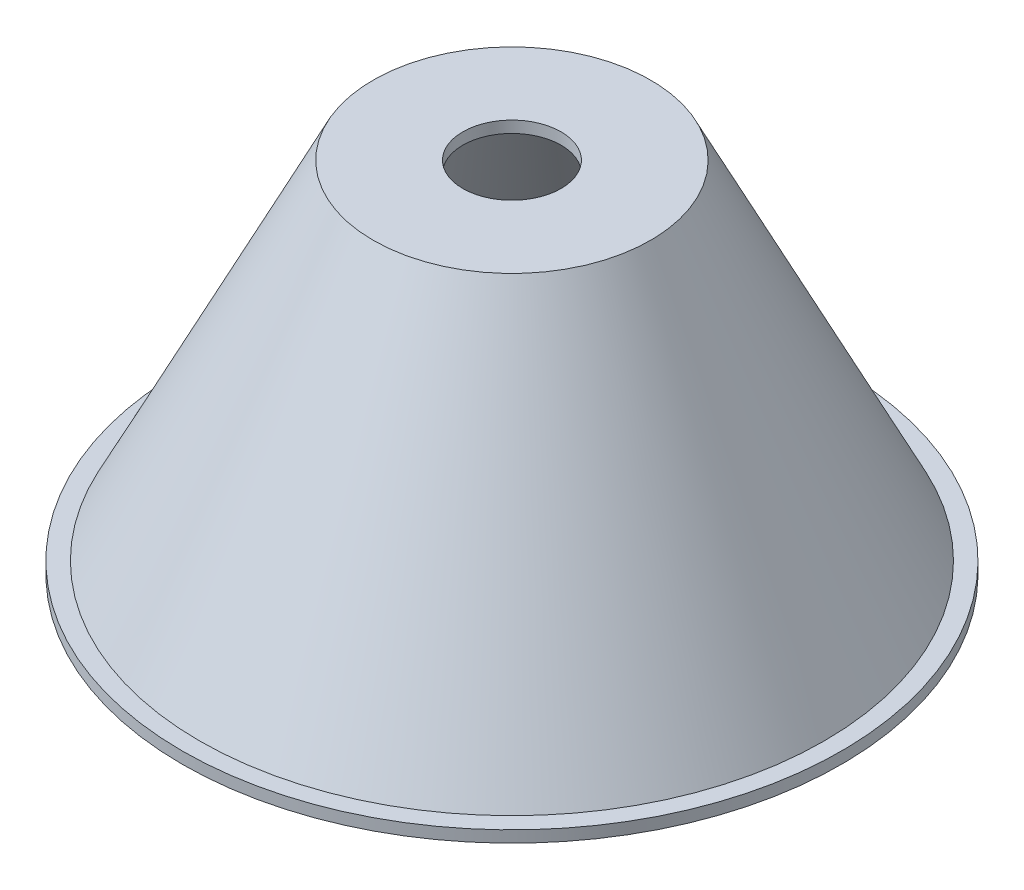
SolidWorks part; units mm, degrees
material "Polyether Polyol"
ref_plane "Front Plane" through (0, 0, 0) normal (0, 0, 1) x (1, 0, 0)
ref_plane "Top Plane" through (0, 0, 0) normal (0, 1, 0) x (1, 0, 0)
ref_plane "Right Plane" through (0, 0, 0) normal (1, 0, 0) x (0, 0, -1)
sketch "Sketch1" plane through (0, 0, 0) normal (0, 1, 0) x (1, 0, 0)
  circle A0 centre (0, 0) radius 28.5
  dimension "D1" = 57
extrude "Boss-Extrude1" add sketch "Sketch1" along normal blind 1
ref_plane "Plane1" through (0, 31, 0) normal (0, 1, 0) x (1, 0, 0)
sketch "Sketch3" plane through (0, 31, 0) normal (0, 1, 0) x (1, 0, 0)
  circle A0 centre (0, 0) radius 12
  dimension "D1" = 24
sketch "Sketch8" plane through (0, 1, 0) normal (0, 1, 0) x (1, 0, 0)
  circle A0 centre (0, 0) radius 27
  circle A1 centre (0, 0) radius 28.5 construction
  dimension "D1" = 1.5
loft "Loft2" add profiles "Sketch8", "Sketch3"
sketch "Sketch9" plane through (0, 0, 0) normal (0, -1, 0) x (1, 0, 0)
  circle A0 centre (0, 0) radius 25.75
  circle A1 centre (0, 0) radius 28.5 construction
  dimension "D1" = 2.75
extrude "Cut-Extrude1" cut sketch "Sketch9" against normal blind 30 draft 25
sketch "Sketch10" plane through (0, 30, 0) normal (0, -1, 0) x (1, 0, 0)
  circle A0 centre (0, 0) radius 4.25
  dimension "D1" = 8.5
extrude "Cut-Extrude2" cut sketch "Sketch10" against normal blind 5
